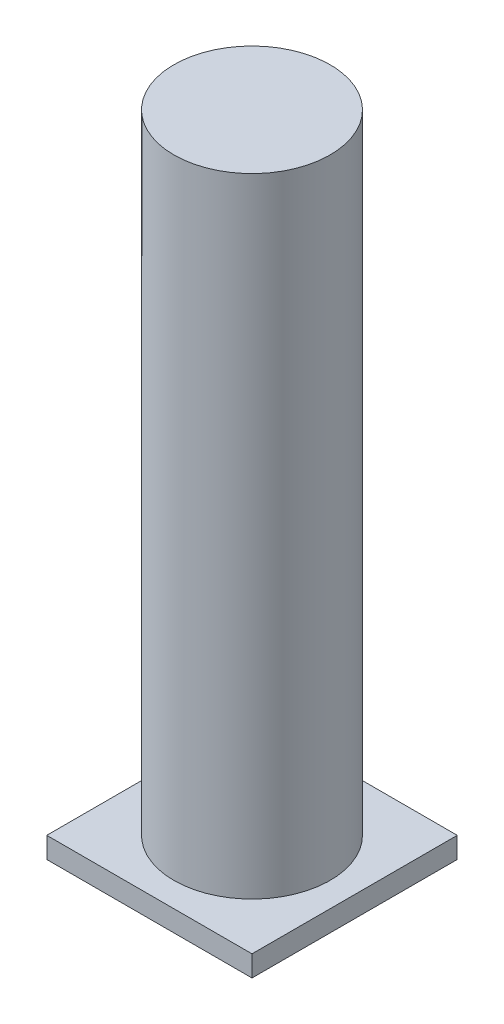
SolidWorks part; units mm, degrees
ref_plane "Front Plane" through (0, 0, 0) normal (0, 0, 1) x (1, 0, 0)
ref_plane "Top Plane" through (0, 0, 0) normal (0, 1, 0) x (1, 0, 0)
ref_plane "Right Plane" through (0, 0, 0) normal (1, 0, 0) x (0, 0, -1)
sketch "Sketch1" plane through (0, 0, 0) normal (0, 1, 0) x (1, 0, 0)
  line L1 (-2.45, 2.45) -> (2.45, 2.45)
  line L2 (-2.45, 2.45) -> (-2.45, -2.45)
  line L3 (-2.45, -2.45) -> (2.45, -2.45)
  line L4 (2.45, 2.45) -> (2.45, -2.45)
  line L5 (-2.45, 2.45) -> (2.45, -2.45) construction
  line L6 (-2.45, -2.45) -> (2.45, 2.45) construction
  point P0 (0, 0)
  dimension "D1" = 4.9
  dimension "D2" = 4.9
extrude "Boss-Extrude1" add sketch "Sketch1" along normal blind 0.5
sketch "Sketch2" plane through (0, 0.5, 0) normal (0, 1, 0) x (1, 0, 0)
  circle A0 centre (0, 0) radius 1.8656
extrude "Boss-Extrude3" add sketch "Sketch2" along normal blind 15
